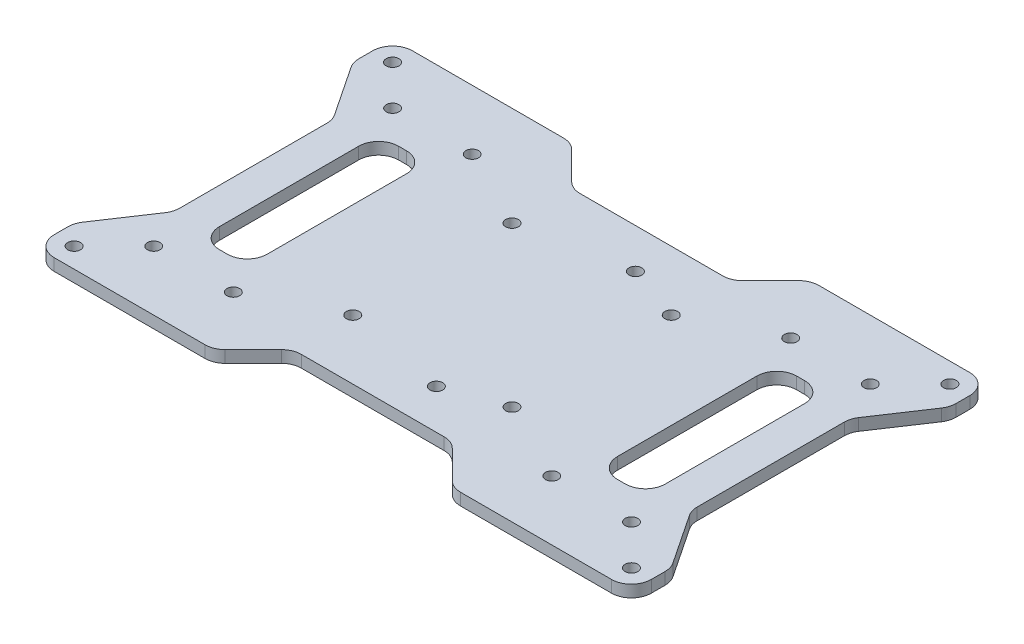
SolidWorks part; units mm, degrees
ref_plane "Alzado" through (0, 0, 0) normal (0, 0, 1) x (1, 0, 0)
ref_plane "Planta" through (0, 0, 0) normal (0, 1, 0) x (1, 0, 0)
ref_plane "Vista lateral" through (0, 0, 0) normal (1, 0, 0) x (0, 0, -1)
sketch "Croquis1" plane through (0, 0, 0) normal (0, 1, 0) x (1, 0, 0)
  line L1 (-75, 45) -> (75, 45)
  line L2 (-75, 45) -> (-75, -45)
  line L3 (-75, -45) -> (75, -45)
  line L4 (75, 45) -> (75, -45)
  line L5 (-75, 45) -> (75, -45) construction
  line L6 (-75, -45) -> (75, 45) construction
  line L7 (-60, 30) -> (60, 30) construction
  line L8 (-60, 30) -> (-60, -30) construction
  line L9 (-60, -30) -> (60, -30) construction
  line L10 (60, 30) -> (60, -30) construction
  line L11 (-60, 30) -> (60, -30) construction
  line L12 (-60, -30) -> (60, 30) construction
  circle A0 centre (-60, 30) radius 1.5875
  circle A1 centre (-60, -30) radius 1.5875
  circle A2 centre (60, -30) radius 1.5875
  circle A3 centre (60, 30) radius 1.5875
  point P0 (0, 0)
  point P6 (0, 0)
  dimension "D5" = 3.175
  dimension "D1" = 90
  dimension "D2" = 150
  dimension "D3" = 120
  dimension "D4" = 60
extrude "Saliente-Extruir1" add sketch "Croquis1" along normal blind 3
sketch "Croquis2" plane through (0, 3, 0) normal (0, 1, 0) x (1, 0, 0)
  line L1 (-40, -30) -> (-60, -30) construction
  line L2 (-40, -30) -> (-40, 30) construction
  line L3 (-40, 30) -> (-60, 30) construction
  line L4 (-60, -30) -> (-60, 30) construction
  line L5 (-40, -30) -> (-60, 30) construction
  line L6 (-40, 30) -> (-60, -30) construction
  line L7 (40, -30) -> (60, -30) construction
  line L8 (40, -30) -> (40, 30) construction
  line L9 (40, 30) -> (60, 30) construction
  line L10 (60, -30) -> (60, 30) construction
  line L11 (40, -30) -> (60, 30) construction
  line L12 (40, 30) -> (60, -30) construction
  circle A0 centre (-60, -30) radius 1.5875 construction
  circle A1 centre (-40, 30) radius 1.5875
  circle A2 centre (-40, -30) radius 1.5875
  circle A3 centre (40, -30) radius 1.5875
  circle A4 centre (40, 30) radius 1.5875
  circle A5 centre (-60, 30) radius 1.5875 construction
  point P0 (-50, 0)
  point P9 (50, 0)
  dimension "D1" = 20
extrude "Cortar-Extruir1" cut sketch "Croquis2" against normal blind 3
sketch "Croquis3" plane through (0, 3, 0) normal (0, 1, 0) x (1, 0, 0)
  line L0 (6, 25) -> (6, -25) construction
  circle A0 centre (6, -25) radius 1.6
  circle A1 centre (6, 25) radius 1.6
  point P4 (6, 0)
  dimension "D1" = 3.2
  dimension "D2" = 6
  dimension "D3" = 50
extrude "Anclaje_Banda" cut sketch "Croquis3" against normal blind 10
sketch "Croquis4" plane through (0, 3, 0) normal (0, 1, 0) x (1, 0, 0)
  line L1 (20, -20) -> (-20, -20) construction
  line L2 (20, -20) -> (20, 20) construction
  line L3 (20, 20) -> (-20, 20) construction
  line L4 (-20, -20) -> (-20, 20) construction
  line L5 (20, -20) -> (-20, 20) construction
  line L6 (20, 20) -> (-20, -20) construction
  line L7 (75, 45) -> (-75, 45) construction
  line L8 (-6, 45) -> (6, 45) construction
  line L9 (-6, 45) -> (-6, -45) construction
  line L10 (-6, -45) -> (6, -45) construction
  line L11 (6, 45) -> (6, -45) construction
  line L12 (-6, 45) -> (6, -45) construction
  line L13 (-6, -45) -> (6, 45) construction
  circle A0 centre (20, -20) radius 1.6
  circle A1 centre (-20, -20) radius 1.6
  circle A2 centre (-20, 20) radius 1.6
  circle A3 centre (20, 20) radius 1.6
  circle A4 centre (6, 25) radius 1.6 construction
  point P10 (0, 0)
  point P17 (0, 0)
  dimension "D3" = 12
  dimension "D1" = 40
extrude "Espacio_Centro" cut sketch "Croquis4" against normal blind 10
sketch "Croquis5" plane through (0, 3, 0) normal (0, 1, 0) x (1, 0, 0)
  line L1 (-70, 40) -> (70, 40) construction
  line L2 (-70, 40) -> (-70, -40) construction
  line L3 (-70, -40) -> (70, -40) construction
  line L4 (70, 40) -> (70, -40) construction
  line L5 (-70, 40) -> (70, -40) construction
  line L6 (-70, -40) -> (70, 40) construction
  circle A0 centre (-70, 40) radius 1.6
  circle A1 centre (70, 40) radius 1.6
  circle A2 centre (70, -40) radius 1.6
  circle A3 centre (-70, -40) radius 1.6
  point P0 (0, 0)
  dimension "D1" = 3.2
  dimension "D2" = 80
  dimension "D3" = 140
extrude "Espacio_externo" cut sketch "Croquis5" against normal blind 10
sketch "Croquis6" plane through (0, 3, 0) normal (0, 1, 0) x (1, 0, 0)
  line L0 (-75, 35) -> (-65, 20)
  line L1 (-75, 45) -> (-75, -45) construction
  line L2 (-65, 20) -> (-65, -20)
  line L3 (-65, -20) -> (-75, -35)
  line L4 (-75, 35) -> (-75, -35)
  line L5 (0, 45) -> (0, -45) construction
  line L6 (75, 45) -> (-75, 45) construction
  line L7 (-75, -45) -> (75, -45) construction
  line L8 (75, 35) -> (75, -35)
  line L9 (65, -20) -> (75, -35)
  line L10 (65, 20) -> (65, -20)
  line L11 (75, 35) -> (65, 20)
  line L12 (56, -22.5) -> (44, 22.5) construction
  line L13 (-56, 22.5) -> (-44, 22.5)
  line L14 (-56, 22.5) -> (-56, -22.5)
  line L15 (-56, -22.5) -> (-44, -22.5)
  line L16 (-44, 22.5) -> (-44, -22.5)
  line L17 (-56, 22.5) -> (-44, -22.5) construction
  line L18 (-56, -22.5) -> (-44, 22.5) construction
  line L19 (56, 22.5) -> (44, -22.5) construction
  line L20 (44, 22.5) -> (44, -22.5)
  line L21 (56, -22.5) -> (44, -22.5)
  line L22 (56, 22.5) -> (56, -22.5)
  line L23 (56, 22.5) -> (44, 22.5)
  line L24 (-30, 45) -> (-20, 35)
  line L25 (-20, 35) -> (20, 35)
  line L26 (20, 35) -> (30, 45)
  line L27 (-20, 0) -> (20, 0) construction
  line L28 (20, -35) -> (30, -45)
  line L29 (-20, -35) -> (20, -35)
  line L30 (-30, -45) -> (-20, -35)
  line L31 (-30, 45) -> (30, 45)
  line L32 (-30, -45) -> (30, -45)
  point P4 (-65, 0)
  point P19 (-50, 0)
  point P24 (0, 35)
  point P29 (50, 0)
  dimension "D1" = 10
  dimension "D2" = 10
  dimension "D3" = 40
  dimension "D4" = 15
  dimension "D5" = 12
  dimension "D6" = 45
  dimension "D7" = 60
  dimension "D8" = 10
  dimension "D9" = 40
extrude "Quita_peso" cut sketch "Croquis6" against normal blind 10
fillet "Redondeo1" radius 5 28 edges at (44, 1.5, 22.5) (44, 1.5, -22.5) (56, 1.5, -22.5) (56, 1.5, 22.5) (-44, 1.5, 22.5) (-56, 1.5, 22.5) (-56, 1.5, -22.5) (-44, 1.5, -22.5) (75, 1.5, -45) (75, 1.5, -35) (65, 1.5, -20) (65, 1.5, 20) (75, 1.5, 35) (75, 1.5, 45) (-75, 1.5, 45) (-75, 1.5, 35) (-65, 1.5, 20) (-65, 1.5, -20) (-75, 1.5, -35) (-75, 1.5, -45) (30, 1.5, 45) (20, 1.5, 35) (-20, 1.5, 35) (-30, 1.5, 45) (30, 1.5, -45) (20, 1.5, -35) (-20, 1.5, -35) (-30, 1.5, -45)
